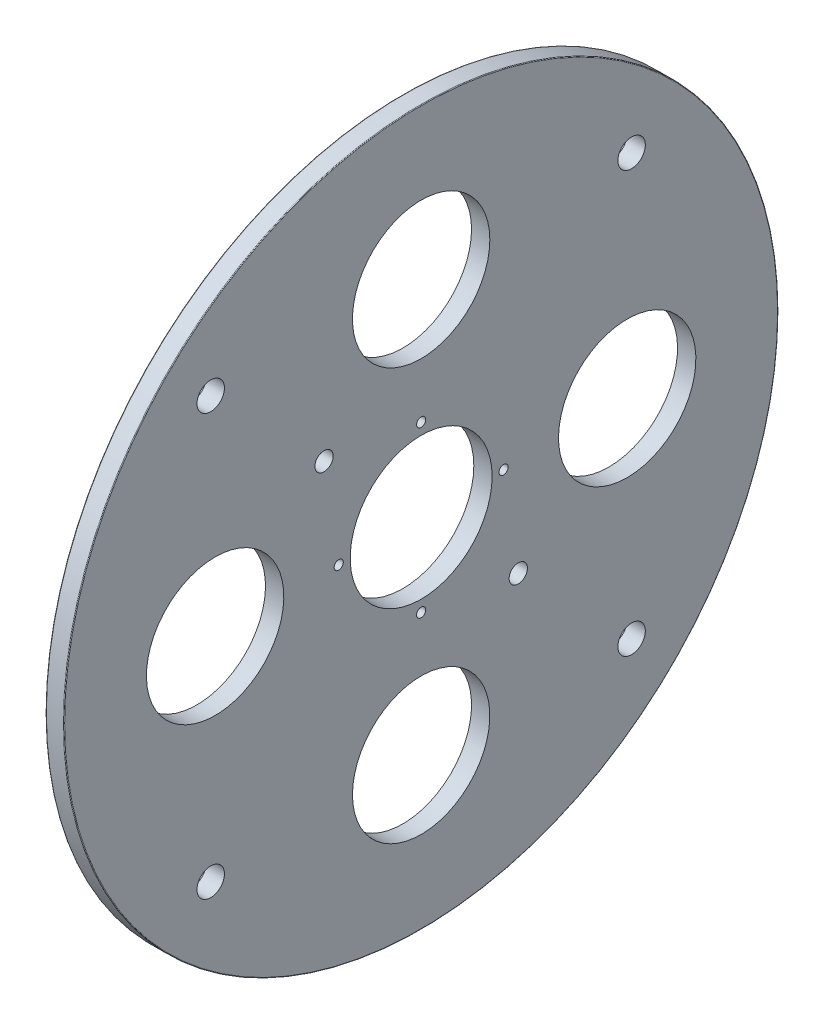
SolidWorks part; units mm, degrees
material "1060 合金"
ref_plane "前视基准面" through (0, 0, 0) normal (0, 0, 1) x (1, 0, 0)
ref_plane "上视基准面" through (0, 0, 0) normal (0, 1, 0) x (1, 0, 0)
ref_plane "右视基准面" through (0, 0, 0) normal (1, 0, 0) x (0, 0, -1)
sketch "草图1" plane through (0, 0, 0) normal (1, 0, 0) x (0, 0, -1)
  circle A0 centre (0, 0) radius 156
extrude "凸台-拉伸1" add sketch "草图1" along normal blind 8
sketch "草图2" plane through (8, 0, 0) normal (1, 0, 0) x (0, 0, -1)
  circle A0 centre (0, 0) radius 31
extrude "切除-拉伸1" cut sketch "草图2" against normal blind 10 contours A0
sketch "草图3" plane through (8, 0, 0) normal (1, 0, 0) x (0, 0, -1)
  circle A0 centre (0, 85) radius 35
extrude "切除-拉伸2" [suppressed] cut sketch "草图3" against normal blind 6 contours A0
pattern_circular "阵列(圆周)1" [suppressed] count 4 over 360
sketch "草图4" plane through (8, 0, 0) normal (1, 0, 0) x (0, 0, -1)
  circle A1 centre (91.9239, 91.9239) radius 6
extrude "切除-拉伸3" cut sketch "草图4" against normal blind 10
pattern_circular "阵列(圆周)2" count 4 over 360 about axis through (0, 0, 0) along (1, 0, 0) of "切除-拉伸3"
sketch "草图6" plane through (8, 0, 0) normal (1, 0, 0) x (0, 0, -1)
  circle A0 centre (0, 36) radius 2
extrude "切除-拉伸5" cut sketch "草图6" against normal blind 10 contours A0
pattern_circular "阵列(圆周)4" count 4 over 360 about axis through (0, 0, 0) along (1, 0, 0) of "切除-拉伸5"
fillet "圆角1" radius 0.3 2 edges at (0, 0, -156) (8, 0, -156)
sketch "草图7" plane through (8, 0, 0) normal (1, 0, 0) x (0, 0, -1)
  circle A4 centre (-56.5685, 56.5685) radius 4
extrude "切除-拉伸6" [suppressed] cut sketch "草图7" against normal blind 10
pattern_circular "阵列(圆周)5" [suppressed] count 4 over 360
sketch "草图8" plane through (8, 0, 0) normal (1, 0, 0) x (0, 0, -1)
  circle A3 centre (42.4264, -42.4264) radius 4
extrude "切除-拉伸7" cut sketch "草图8" against normal blind 10
sketch "草图9" plane through (8, 0, 0) normal (1, 0, 0) x (0, 0, -1)
  circle A0 centre (0, 90) radius 30
extrude "切除-拉伸8" cut sketch "草图9" against normal blind 10
pattern_circular "阵列(圆周)6" count 4 over 360 about axis through (0, 0, 0) along (1, 0, 0) of "切除-拉伸8"
pattern_circular "阵列(圆周)7" count 2 over 360 about axis through (0, 0, 0) along (1, 0, 0) of "切除-拉伸7"
